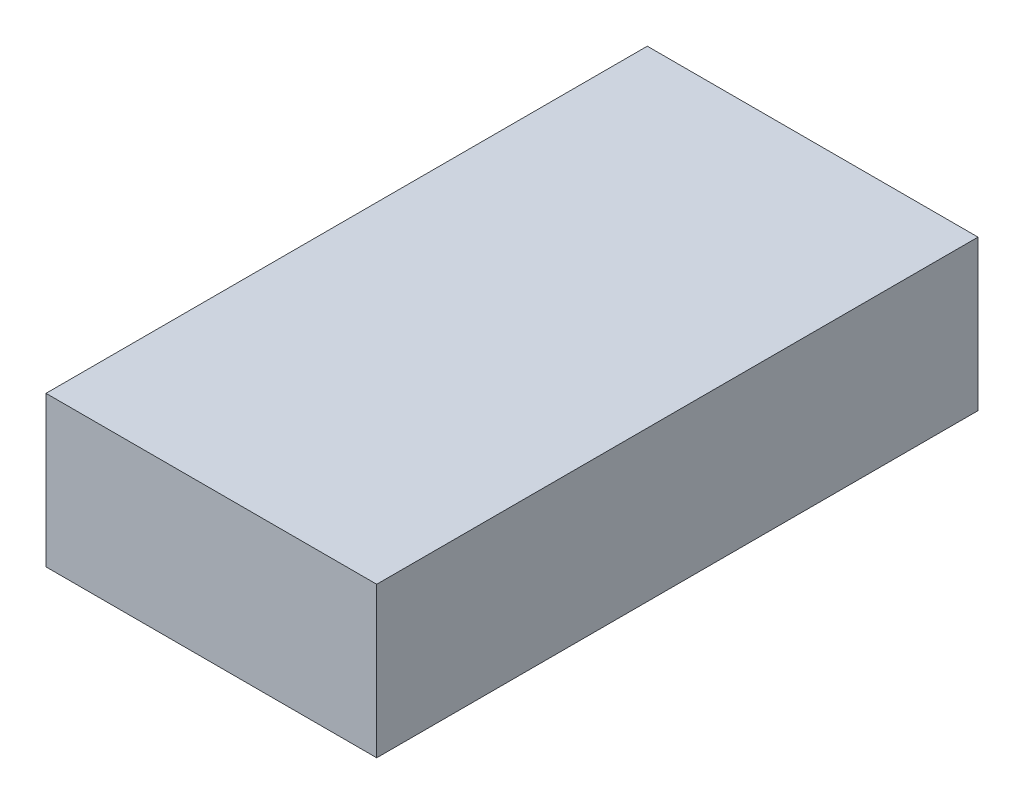
SolidWorks part; units mm, degrees
ref_plane "Front Plane" through (0, 0, 0) normal (0, 0, 1) x (1, 0, 0)
ref_plane "Top Plane" through (0, 0, 0) normal (0, 1, 0) x (1, 0, 0)
ref_plane "Right Plane" through (0, 0, 0) normal (1, 0, 0) x (0, 0, -1)
sketch "Sketch1" plane through (0, 0, 0) normal (0, 0, 1) x (1, 0, 0)
  line L0 (0, 0) -> (110, 0)
  line L1 (0, 0) -> (0, 50)
  line L2 (0, 50) -> (110, 50)
  line L3 (110, 50) -> (110, 0)
  dimension "D1" = 110
  dimension "D2" = 50
extrude "Boss-Extrude1" add sketch "Sketch1" along normal blind 200
